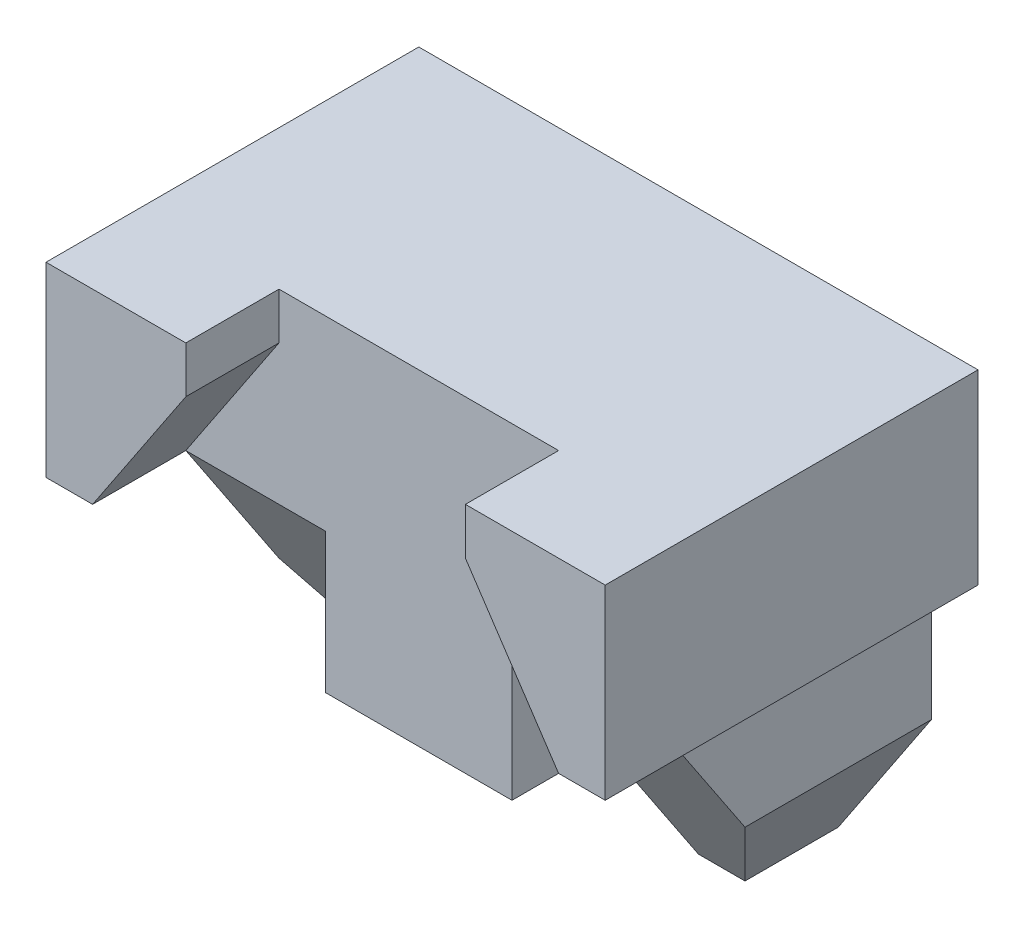
SolidWorks part; units mm, degrees
ref_plane "Front Plane" through (0, 0, 0) normal (0, 0, 1) x (1, 0, 0)
ref_plane "Top Plane" through (0, 0, 0) normal (0, 1, 0) x (1, 0, 0)
ref_plane "Right Plane" through (0, 0, 0) normal (1, 0, 0) x (0, 0, -1)
sketch "Sketch1" plane through (0, 0, 0) normal (0, 0, 1) x (1, 0, 0)
  line L0 (0, 0) -> (10, 0)
  line L1 (10, 0) -> (10, 30)
  line L2 (10, 30) -> (50, 30)
  line L3 (50, 30) -> (50, 0)
  line L4 (50, 0) -> (60, 0)
  line L5 (60, 0) -> (80, 30)
  line L6 (80, 30) -> (80, 60)
  line L7 (80, 60) -> (90, 60)
  line L8 (90, 60) -> (90, 100)
  line L9 (90, 100) -> (-30, 100)
  line L10 (-30, 100) -> (-30, 60)
  line L11 (-30, 60) -> (-20, 60)
  line L12 (-20, 60) -> (-20, 30)
  line L13 (-20, 30) -> (0, 0)
  dimension "D1" = 100
  dimension "D2" = 40
  dimension "D3" = 10
  dimension "D4" = 10
  dimension "D5" = 30
  dimension "D6" = 40
  dimension "D7" = 100
  dimension "D8" = 120
  dimension "D9" = 30
  dimension "D10" = 10
extrude "Boss-Extrude1" add sketch "Sketch1" along normal blind 60
sketch "Sketch2" plane through (0, 0, 60) normal (0, 0, 1) x (1, 0, 0)
  line L0 (-20, 60) -> (0, 90)
  line L1 (0, 90) -> (0, 100)
  line L2 (90, 100) -> (-30, 100) construction
  line L3 (0, 100) -> (-30, 100)
  line L4 (-30, 100) -> (-30, 60)
  line L5 (-30, 60) -> (-20, 60)
  line L6 (80, 60) -> (60, 90)
  line L7 (60, 90) -> (60, 100)
  line L8 (60, 100) -> (90, 100)
  line L9 (90, 100) -> (90, 60)
  line L10 (90, 60) -> (80, 60)
  dimension "D1" = 30
  dimension "D2" = 10
  dimension "D3" = 30
  dimension "D4" = 10
extrude "Boss-Extrude2" add sketch "Sketch2" along normal blind 20
sketch "Sketch3" plane through (-20, 0, 0) normal (-1, 0, 0) x (0, 0, 1)
  line L0 (60, 60) -> (20, 0)
  line L1 (20, 0) -> (60, 0)
  line L2 (60, 0) -> (60, 60)
  point P4 (0, -3.5118)
  dimension "D1" = 40
extrude "Cut-Extrude1" cut sketch "Sketch3" against normal blind 30
sketch "Sketch4" plane through (80, 0, 0) normal (1, 0, 0) x (0, 0, -1)
  line L0 (-60, 60) -> (-20, 0)
  line L1 (-20, 0) -> (-60, 0)
  line L2 (-60, 0) -> (-60, 60)
  line L3 (-60, 0) -> (-60, 30) construction
  point P5 (0, 0)
  point P6 (-60, 0)
  dimension "D1" = 40
extrude "Cut-Extrude2" cut sketch "Sketch4" against normal blind 30
